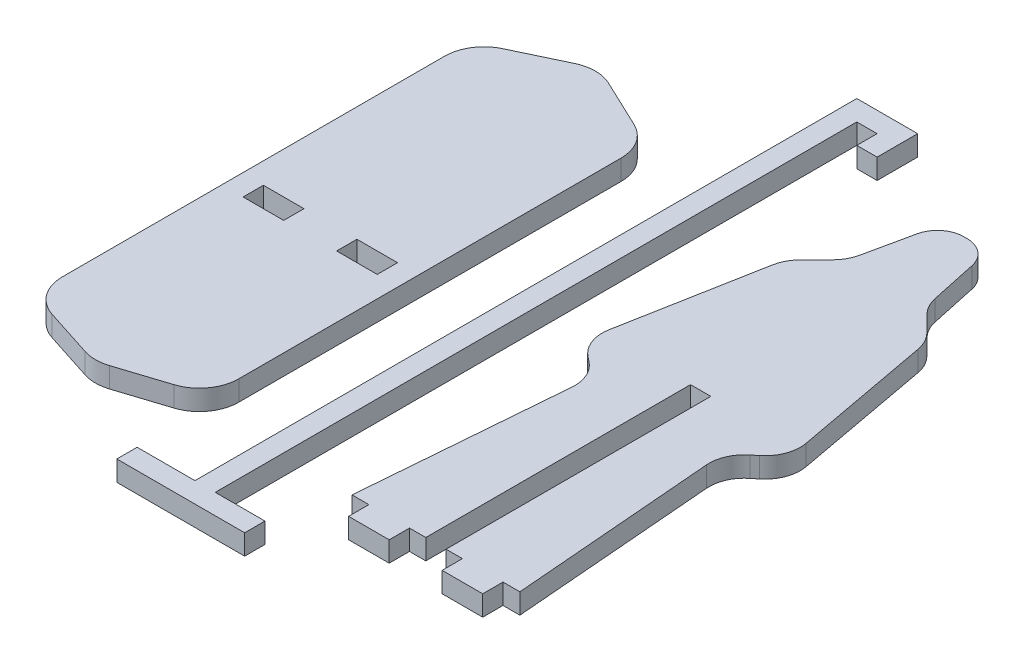
SolidWorks part; units mm, degrees
ref_plane "Front Plane" through (0, 0, 0) normal (0, 0, 1) x (1, 0, 0)
ref_plane "Top Plane" through (0, 0, 0) normal (0, 1, 0) x (1, 0, 0)
ref_plane "Right Plane" through (0, 0, 0) normal (1, 0, 0) x (0, 0, -1)
sketch "disc" plane through (0, 0, 0) normal (0, 1, 0) x (1, 0, 0)
  circle A0 centre (0, 0) radius 50 construction
  dimension "D1" = 100
sketch "figurines" plane through (0, 0, 0) normal (0, 1, 0) x (1, 0, 0)
  line L1 (-1.8873, 0.7994) -> (-5.5484, 17.0707)
  line L2 (-5.5484, 17.0707) -> (-1.8873, 19.337)
  line L3 (-1.8873, 19.337) -> (-7.7824, 32.5284)
  line L5 (-18.339, 32.5284) -> (-31.2337, 20.8479)
  line L6 (-31.2337, 20.8479) -> (-24.7543, 15.153)
  line L7 (-24.7543, 15.153) -> (-19.2627, 17.0707)
  line L8 (-19.2627, 17.0707) -> (-21.2966, 0.7994)
  line L11 (2.871, 0.2607) -> (4.6659, 14.44)
  line L12 (4.6659, 14.44) -> (0.6562, 17.6942)
  line L13 (0.6562, 17.6942) -> (6.5254, 32.4546)
  line L15 (14.603, 32.4546) -> (19.1938, 17.6942)
  line L16 (19.1938, 17.6942) -> (16.6488, 14.5585)
  line L17 (16.6488, 14.5585) -> (18.7028, 0.2607)
  line L19 (-18.339, 32.5284) -> (-15.7657, 38.4467)
  line L20 (-15.7657, 38.4467) -> (-11.9461, 40.8113)
  line L21 (-11.9461, 40.8113) -> (-7.7824, 36.2147)
  line L22 (-7.7824, 36.2147) -> (-7.7824, 32.5284)
  line L23 (6.5254, 32.4546) -> (7.862, 40.6794)
  line L24 (7.862, 40.6794) -> (13.7313, 40.6794)
  line L25 (13.7313, 40.6794) -> (14.603, 32.4546)
  line L26 (-21.2966, 0.7994) -> (-19.902, 0.7994)
  line L27 (-19.902, 0.7994) -> (-19.902, -1.5006)
  line L28 (-19.902, -1.5006) -> (-15.902, -1.5006)
  line L29 (-15.902, -1.5006) -> (-15.902, 0.7994)
  line L30 (-15.902, 0.7994) -> (-12.9286, 0.7994)
  line L31 (-12.9286, 0.7994) -> (-12.9286, 15.7994)
  line L32 (-12.9286, 15.7994) -> (-10.6286, 15.7994)
  line L33 (-10.6286, 15.7994) -> (-10.6286, 0.7994)
  line L34 (-10.6286, 0.7994) -> (-7.902, 0.7994)
  line L35 (-7.902, 0.7994) -> (-7.902, -1.5006)
  line L36 (-7.902, -1.5006) -> (-3.902, -1.5006)
  line L37 (-3.902, -1.5006) -> (-3.902, 0.7994)
  line L38 (-3.902, 0.7994) -> (-1.8873, 0.7994)
  line L39 (2.871, 0.2607) -> (4.6659, 0.2607)
  line L40 (4.6659, 0.2607) -> (4.6659, -2.0393)
  line L41 (4.6659, -2.0393) -> (7.6659, -2.0393)
  line L42 (7.6659, -2.0393) -> (7.6659, 0.2607)
  line L43 (7.6659, 0.2607) -> (9.7579, 0.2607)
  line L44 (9.7579, 0.2607) -> (9.7579, 15.2607)
  line L45 (9.7579, 15.2607) -> (12.0579, 15.2607)
  line L46 (12.0579, 15.2607) -> (12.0579, 0.2607)
  line L47 (12.0579, 0.2607) -> (13.6659, 0.2607)
  line L48 (13.6659, 0.2607) -> (13.6659, -2.0393)
  line L49 (13.6659, -2.0393) -> (16.6659, -2.0393)
  line L50 (16.6659, -2.0393) -> (16.6659, 0.2607)
  line L51 (16.6659, 0.2607) -> (18.7028, 0.2607)
  line L52 (-13.8596, -29.0558) -> (18.1404, -29.0558) construction
  line L53 (-13.8596, -23.0558) -> (18.1404, -23.0558)
  line L54 (-13.8596, -35.0558) -> (18.1404, -35.0558)
  line L55 (-70.1129, 7.9716) -> (-42.1129, 7.9716) construction
  line L56 (-5.8596, -30.2058) -> (-1.8596, -30.2058)
  line L57 (-5.8596, -30.2058) -> (-5.8596, -27.9058)
  line L58 (-5.8596, -27.9058) -> (-1.8596, -27.9058)
  line L59 (-1.8596, -30.2058) -> (-1.8596, -27.9058)
  line L60 (-5.8596, -30.2058) -> (-1.8596, -27.9058) construction
  line L61 (-5.8596, -27.9058) -> (-1.8596, -30.2058) construction
  line L62 (6.1404, -30.2058) -> (10.1404, -30.2058)
  line L63 (6.1404, -30.2058) -> (6.1404, -27.9058)
  line L64 (6.1404, -27.9058) -> (10.1404, -27.9058)
  line L65 (10.1404, -30.2058) -> (10.1404, -27.9058)
  line L66 (6.1404, -30.2058) -> (10.1404, -27.9058) construction
  line L67 (6.1404, -27.9058) -> (10.1404, -30.2058) construction
  line L68 (-70.1129, 15.9716) -> (-42.1129, 15.9716)
  line L69 (-70.1129, -0.0284) -> (-42.1129, -0.0284)
  line L71 (-54.9629, 10.9716) -> (-57.2629, 10.9716)
  line L72 (-54.9629, 10.9716) -> (-54.9629, 13.9716)
  line L73 (-54.9629, 13.9716) -> (-57.2629, 13.9716)
  line L74 (-57.2629, 10.9716) -> (-57.2629, 13.9716)
  line L75 (-54.9629, 10.9716) -> (-57.2629, 13.9716) construction
  line L76 (-54.9629, 13.9716) -> (-57.2629, 10.9716) construction
  line L77 (-57.2629, 1.9716) -> (-54.9629, 1.9716)
  line L78 (-57.2629, 1.9716) -> (-57.2629, 4.9716)
  line L79 (-57.2629, 4.9716) -> (-54.9629, 4.9716)
  line L80 (-54.9629, 1.9716) -> (-54.9629, 4.9716)
  line L81 (-57.2629, 1.9716) -> (-54.9629, 4.9716) construction
  line L82 (-57.2629, 4.9716) -> (-54.9629, 1.9716) construction
  arc A0 (-13.8596, -23.0558) -> (-13.8596, -35.0558) centre (-13.8596, -29.0558) ccw
  arc A1 (18.1404, -35.0558) -> (18.1404, -23.0558) centre (18.1404, -29.0558) ccw
  arc A2 (-70.1129, 15.9716) -> (-70.1129, -0.0284) centre (-70.1129, 7.9716) ccw
  arc A3 (-42.1129, -0.0284) -> (-42.1129, 15.9716) centre (-42.1129, 7.9716) ccw
  point P34 (2.1404, -29.0558)
  point P53 (-3.8596, -29.0558)
  point P58 (8.1404, -29.0558)
  point P65 (-56.1129, 7.9716)
  point P70 (-56.1129, 3.4716)
  point P75 (-56.1129, 12.4716)
  point P80 (0, 0)
  point P81 (0, 0)
  point P82 (-103.613, 23.5352)
  dimension "D15" = 6
  dimension "D21" = 8
  dimension "D1" = 2.3
  dimension "D2" = 2.3
  dimension "D3" = 4
  dimension "D4" = 2.3
  dimension "D5" = 4
  dimension "D6" = 3
  dimension "D7" = 2.3
  dimension "D8" = 2.3
  dimension "D9" = 2.3
  dimension "D10" = 3
  dimension "D11" = 15
  dimension "D12" = 32
  dimension "D13" = 15
  dimension "D14" = 8
  dimension "D16" = 2.3
  dimension "D17" = 4
  dimension "D18" = 4
  dimension "D19" = 8
  dimension "D20" = 28
  dimension "D22" = 6
  dimension "D23" = 4
  dimension "D24" = 3
  dimension "D25" = 3
  dimension "D26" = 2.3
  dimension "D27" = 2.3
  dimension "D28" = 3
  dimension "D29" = 3
sketch "pylone" plane through (0, 0, 0) normal (0, 1, 0) x (1, 0, 0)
  line L0 (4, 45) -> (-4, 45)
  line L1 (-4, -45) -> (4, -45) construction
  line L2 (-4, -45) -> (-4, 45) construction
  line L3 (-4, 45) -> (4, 45) construction
  line L4 (4, -45) -> (4, 45) construction
  line L5 (-4, -45) -> (4, 45) construction
  line L6 (-4, 45) -> (4, -45) construction
  line L8 (-16, 45) -> (-16, 37)
  line L9 (-16, 37) -> (-4, 33)
  line L10 (-4, 33) -> (-4, -35)
  line L11 (-4, -35) -> (-14, -45)
  line L13 (-4, -45) -> (-1.15, -45)
  line L14 (-1.15, -45) -> (-1.15, -39)
  line L15 (-1.15, -39) -> (1.15, -39)
  line L16 (1.15, -39) -> (1.15, -45)
  line L17 (1.15, -45) -> (4, -45)
  line L19 (14, -45) -> (4, -35)
  line L20 (4, -35) -> (4, 45)
  line L21 (-14, -45) -> (-11, -45)
  line L22 (-11, -45) -> (-11, -47.3)
  line L23 (-11, -47.3) -> (-6, -47.3)
  line L24 (-6, -47.3) -> (-6, -45)
  line L25 (-6, -45) -> (-4, -45)
  line L26 (4, -45) -> (6, -45)
  line L27 (6, -45) -> (6, -47.3)
  line L28 (6, -47.3) -> (11, -47.3)
  line L29 (11, -47.3) -> (11, -45)
  line L30 (11, -45) -> (14, -45)
  line L32 (-23.8523, 15.7803) -> (-9.8523, 1.7803) construction
  line L33 (-9.8523, 1.7803) -> (-23.8523, -12.2197) construction
  line L34 (-23.8523, 15.7803) -> (-23.8523, 12.7803)
  line L35 (-23.8523, 12.7803) -> (-26.1523, 12.7803)
  line L36 (-26.1523, 12.7803) -> (-26.1523, 7.7803)
  line L37 (-26.1523, 7.7803) -> (-23.8523, 7.7803)
  line L38 (-23.8523, 7.7803) -> (-23.8523, -4.2197)
  line L39 (-23.8523, -4.2197) -> (-26.1523, -4.2197)
  line L40 (-26.1523, -4.2197) -> (-26.1523, -9.2197)
  line L41 (-26.1523, -9.2197) -> (-23.8523, -9.2197)
  line L42 (-23.8523, -9.2197) -> (-23.8523, -12.2197)
  line L43 (-23.8523, 15.7803) -> (-11.0023, 2.9303)
  line L44 (-11.0023, 2.9303) -> (-17.8523, 2.9303)
  line L45 (-17.8523, 0.6303) -> (-17.8523, 2.9303)
  line L46 (-23.8523, -12.2197) -> (-11.0023, 0.6303)
  line L47 (-11.0023, 0.6303) -> (-17.8523, 0.6303)
  line L48 (-16, 45) -> (-13.7, 45)
  line L49 (-13.7, 45) -> (-13.7, 41)
  line L50 (-13.7, 41) -> (-11.4, 41)
  line L51 (-11.4, 41) -> (-11.4, 45)
  line L52 (-11.4, 45) -> (-4, 45)
  line L53 (21.5835, -10.8439) -> (23.8835, -10.8439)
  line L54 (28.7335, -0.9939) -> (33.7335, -0.9939)
  line L55 (28.7335, -0.9939) -> (28.7335, 1.3061)
  line L56 (28.7335, 1.3061) -> (33.7335, 1.3061)
  line L57 (33.7335, -0.9939) -> (33.7335, 1.3061)
  line L58 (28.7335, -0.9939) -> (33.7335, 1.3061) construction
  line L59 (28.7335, 1.3061) -> (33.7335, -0.9939) construction
  line L60 (23.8835, -5.8439) -> (23.8835, -10.8439)
  line L61 (21.5835, -5.8439) -> (21.5835, -10.8439)
  line L62 (21.5835, -5.8439) -> (23.8835, -5.8439)
  line L63 (11.7335, 1.3061) -> (11.7335, -0.9939)
  line L64 (16.7335, -0.9939) -> (11.7335, -0.9939)
  line L65 (16.7335, 1.3061) -> (11.7335, 1.3061)
  line L66 (16.7335, 1.3061) -> (16.7335, -0.9939)
  line L67 (23.8835, 11.1561) -> (21.5835, 11.1561)
  line L68 (21.5835, 6.1561) -> (21.5835, 11.1561)
  line L69 (23.8835, 6.1561) -> (23.8835, 11.1561)
  line L70 (23.8835, 6.1561) -> (21.5835, 6.1561)
  circle A0 centre (22.7335, 0.1561) radius 15
  point P0 (0, 0)
  point P43 (0, 0)
  point P48 (31.2335, 0.1561)
  point P66 (22.7335, 0.1561)
  dimension "D3" = 30
  dimension "D1" = 90
  dimension "D2" = 8
  dimension "D4" = 2.3
  dimension "D5" = 5
  dimension "D6" = 2.3
  dimension "D7" = 10
  dimension "D8" = 6
  dimension "D9" = 28
  dimension "D10" = 28
  dimension "D11" = 2.3
  dimension "D12" = 5
  dimension "D13" = 12
  dimension "D14" = 12
  dimension "D15" = 2.3
  dimension "D16" = 12.85
  dimension "D17" = 6.85
  dimension "D18" = 8
  dimension "D19" = 12
  dimension "D20" = 12
  dimension "D21" = 2.3
  dimension "D22" = 2.3
  dimension "D23" = 6
  dimension "D24" = 5
  dimension "D25" = 2.3
  dimension "D26" = 4
sketch "skier" plane through (0, 0, 0) normal (0, 1, 0) x (1, 0, 0)
  line L0 (-1.15, 37.5) -> (5.75, 37.5)
  line L2 (-1.15, -37.5) -> (-1.15, 37.5) construction
  line L3 (-1.15, 37.5) -> (1.15, 37.5) construction
  line L7 (5.75, 37.5) -> (5.75, 32.9)
  line L8 (5.75, 32.9) -> (3.45, 32.9)
  line L9 (3.45, 32.9) -> (3.45, 35.2)
  line L10 (3.45, 35.2) -> (1.15, 35.2)
  line L11 (1.15, 35.2) -> (1.15, -37.5)
  line L12 (1.15, -37.5) -> (6.7843, -37.5)
  line L13 (6.7843, -37.5) -> (6.7843, -39.8)
  line L14 (6.7843, -39.8) -> (-7.7025, -39.8)
  line L15 (-7.7025, -39.8) -> (-7.7025, -37.5)
  line L16 (-7.7025, -37.5) -> (-1.15, -37.5)
  line L17 (-1.15, -37.5) -> (-1.15, 37.5)
  line L18 (0, -50) -> (0, 50) construction
  line L23 (-20.5725, 24.9521) -> (-26.1106, 22.3244)
  line L25 (18.6598, -13.1621) -> (18.6598, 13.1621) construction
  line L35 (-18.6598, -13.1621) -> (-18.6598, 13.1621) construction
  line L40 (18.4736, 30) -> (18.8459, 30)
  line L41 (21.7793, 27.6286) -> (22.9222, 22.295)
  line L42 (23.9918, 20.3179) -> (25.8304, 18.462)
  line L43 (26.9217, 16.3764) -> (29.8114, 0.7984)
  line L44 (28.3682, -3.0619) -> (27.7852, -3.5254)
  line L45 (26.2882, -6.9819) -> (28.1689, -30)
  line L46 (28.1689, -30) -> (26.2598, -30)
  line L47 (26.2598, -30) -> (26.2598, -32.3)
  line L48 (26.2598, -32.3) -> (21.6598, -32.3)
  line L49 (21.6598, -32.3) -> (21.6598, -30)
  line L50 (21.6598, -30) -> (19.8098, -30)
  line L51 (19.8098, -30) -> (19.8098, 0)
  line L65 (17.5098, 0) -> (19.8098, 0)
  line L66 (17.5098, -30) -> (17.5098, 0)
  line L67 (15.6598, -30) -> (17.5098, -30)
  line L68 (15.6598, -32.3) -> (15.6598, -30)
  line L69 (11.0598, -32.3) -> (15.6598, -32.3)
  line L70 (11.0598, -30) -> (11.0598, -32.3)
  line L71 (9.1507, -30) -> (11.0598, -30)
  line L72 (11.0313, -6.9819) -> (9.1507, -30)
  line L73 (8.9514, -3.0619) -> (9.5343, -3.5254)
  line L74 (10.3978, 16.3764) -> (7.5082, 0.7984)
  line L75 (13.3277, 20.3179) -> (11.4891, 18.462)
  line L76 (15.5402, 27.6286) -> (14.3973, 22.295)
  line L77 (-28.6598, 18.2932) -> (-28.6598, -25.0212)
  line L82 (-25.5679, -29.2676) -> (-20.0299, -31.0545)
  line L83 (-15.6598, -4.6347) -> (-15.6598, -6.9347)
  line L84 (-26.2598, -4.6347) -> (-21.6598, -4.6347)
  line L85 (-26.2598, -4.6347) -> (-26.2598, -6.9347)
  line L86 (-26.2598, -6.9347) -> (-21.6598, -6.9347)
  line L87 (-21.6598, -4.6347) -> (-21.6598, -6.9347)
  line L88 (-11.0598, -6.9347) -> (-15.6598, -6.9347)
  line L89 (-11.0598, -4.6347) -> (-11.0598, -6.9347)
  line L90 (-11.0598, -4.6347) -> (-15.6598, -4.6347)
  line L91 (-11.7516, -29.2676) -> (-17.2897, -31.0545)
  line L92 (-8.6598, 18.2932) -> (-8.6598, -25.0212)
  line L93 (-16.7471, 24.9521) -> (-11.209, 22.3244)
  arc A0 (26.2882, -6.9819) -> (27.7852, -3.5254) centre (30.2749, -6.6561) cw
  arc A1 (29.8114, 0.7984) -> (28.3682, -3.0619) centre (25.8785, 0.0689) cw
  arc A2 (23.9918, 20.3179) -> (22.9222, 22.295) centre (26.8334, 23.1331) cw
  arc A3 (25.8304, 18.462) -> (26.9217, 16.3764) centre (22.9888, 15.6469) cw
  arc A4 (18.8459, 30) -> (21.7793, 27.6286) centre (18.8459, 27) cw
  arc A5 (18.4736, 30) -> (15.5402, 27.6286) centre (18.4736, 27) ccw
  arc A6 (11.4891, 18.462) -> (10.3978, 16.3764) centre (14.3307, 15.6469) ccw
  arc A7 (13.3277, 20.3179) -> (14.3973, 22.295) centre (10.4861, 23.1331) ccw
  arc A8 (7.5082, 0.7984) -> (8.9514, -3.0619) centre (11.4411, 0.0689) ccw
  arc A9 (11.0313, -6.9819) -> (9.5343, -3.5254) centre (7.0446, -6.6561) ccw
  arc A10 (-17.2897, -31.0545) -> (-20.0299, -31.0545) centre (-18.6598, -26.8081) cw
  arc A11 (-16.7471, 24.9521) -> (-20.5725, 24.9521) centre (-18.6598, 20.921) ccw
  arc A12 (-28.6598, -25.0212) -> (-25.5679, -29.2676) centre (-24.1978, -25.0212) ccw
  arc A13 (-8.6598, -25.0212) -> (-11.7516, -29.2676) centre (-13.1217, -25.0212) cw
  arc A14 (-8.6598, 18.2932) -> (-11.209, 22.3244) centre (-13.1217, 18.2932) ccw
  arc A15 (-26.1106, 22.3244) -> (-28.6598, 18.2932) centre (-24.1978, 18.2932) ccw
  point P0 (0, 0)
  point P25 (0, 0)
  point P31 (18.6598, 0)
  point P34 (16.0484, 30)
  point P53 (18.6598, 0)
  point P77 (18.6598, 0)
  point P83 (18.6598, 30)
  point P92 (-18.6598, -31.4965)
  point P95 (-18.6598, 25.8597)
  point P98 (-28.6598, -28.27)
  point P101 (-8.6598, -28.27)
  point P104 (-8.6598, 21.1149)
  point P107 (-28.6598, 21.1149)
  dimension "D13" = 4
  dimension "D14" = 4
  dimension "D15" = 4
  dimension "D16" = 3
  dimension "D21" = 4.4619
  dimension "D1" = 75
  dimension "D2" = 2.3
  dimension "D3" = 2.3
  dimension "D4" = 2.3
  dimension "D5" = 2.3
  dimension "D6" = 1.15
  dimension "D7" = 2.3
  dimension "D8" = 18.6598
  dimension "D9" = 10
  dimension "D10" = 4.6
  dimension "D11" = 30
  dimension "D12" = 3
  dimension "D17" = 19.0182
  dimension "D18" = 4.6
  dimension "D19" = 2.3
  dimension "D20" = 3
extrude "Boss-Extrude1" add sketch "skier" along normal blind 2.3
